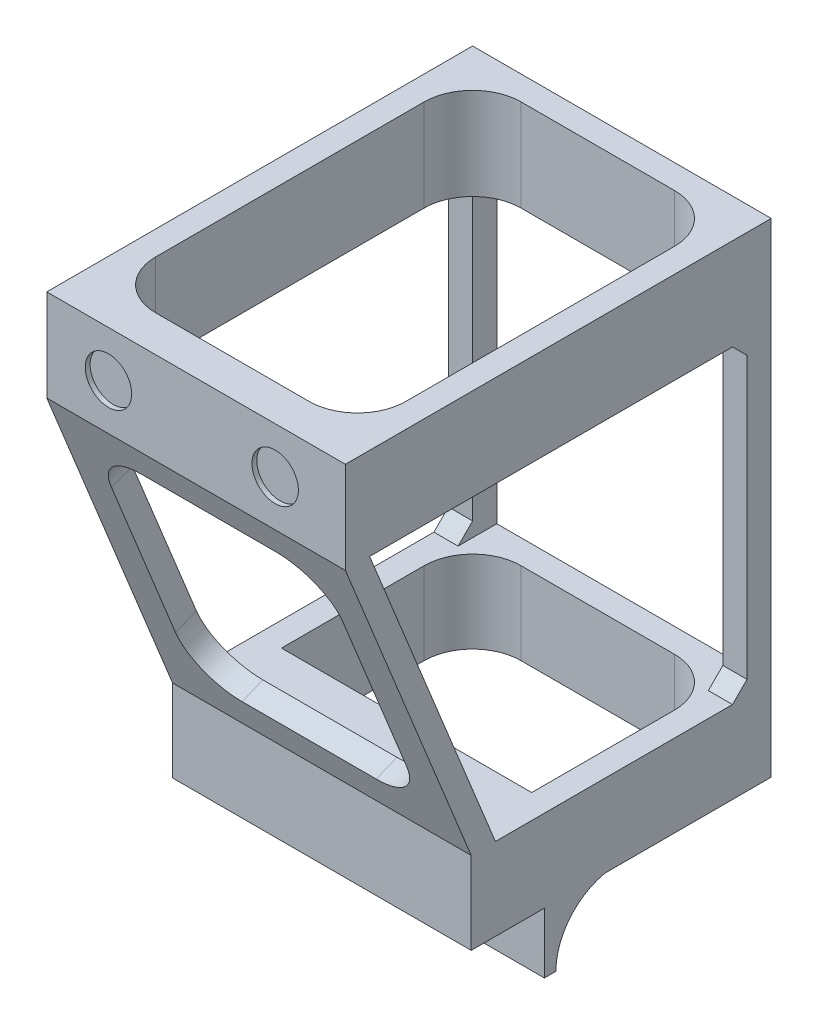
SolidWorks part; units mm, degrees
ref_plane "Front Plane" through (0, 0, 0) normal (1, 0, 0) x (0, 1, 0)
ref_plane "Top Plane" through (0, 0, 0) normal (0, 0, 1) x (0, 1, 0)
ref_plane "Right Plane" through (0, 0, 0) normal (0, 1, 0) x (-1, 0, 0)
sketch "Sketch3" plane through (0, 0, 0) normal (1, 0, 0) x (0, 1, 0)
  line L0 (0, 5) -> (0, 0)
  line L1 (0, 5) -> (17, 5)
  line L2 (17, 5) -> (81, 31)
  line L3 (81, 31) -> (100, 31)
  line L4 (0, 0) -> (17, 0)
  line L5 (17, 0) -> (81, 26)
  line L6 (81, 26) -> (100, 26)
  line L7 (100, 26) -> (100, 31)
  dimension "D1" = 100
  dimension "D2" = 26
  dimension "D3" = 17
  dimension "D4" = 19
  dimension "D5" = 5
extrude "Boss-Extrude1" add sketch "Sketch3" along normal blind 58.71
sketch "Sketch4" plane through (0, 0, 31) normal (0, 0, 1) x (1, 0, 0)
  line L0 (29.27, 23.6763) -> (29.27, 76.7509) construction
  line L1 (58.71, 100) -> (0, 100) construction
  line L7 (0, 81) -> (0, 17) construction
  line L8 (0, 100) -> (0, 81) construction
  circle A0 centre (12.75, 90.5) radius 4.8
  circle A1 centre (47.2, 90.5) radius 4.8
  dimension "D2" = 9.6
  dimension "D3" = 9.6
  dimension "D1" = 9.5
  dimension "D4" = 29.27
  dimension "D5" = 12.75
  dimension "D6" = 16.52
  dimension "D7" = 17.93
extrude "Cut-Extrude1" cut sketch "Sketch4" against normal blind 1
sketch "Sketch5" plane through (0, 0, 5) normal (0, 0, 1) x (1, 0, 0)
  line L0 (29.355, 100) -> (29.355, 58.2947) construction
  line L1 (58.71, 100) -> (0, 100) construction
  line L2 (58.71, 0) -> (0, 0) construction
  line L3 (0, 17) -> (0, 0) construction
  circle A0 centre (21.94, 8.5) radius 4.8
  circle A1 centre (36.94, 8.5) radius 4.8
  dimension "D4" = 9.6
  dimension "D5" = 9.6
  dimension "D1" = 15
  dimension "D2" = 21.94
  dimension "D3" = 8.5
extrude "Cut-Extrude2" cut sketch "Sketch5" against normal blind 1
sketch "Sketch6" plane through (58.71, 0, 0) normal (1, 0, 0) x (0, 1, 0)
  line L0 (81, 26) -> (81, 0)
  line L1 (81, 0) -> (100, 0)
  line L2 (100, 0) -> (100, 26)
  line L3 (81, 26) -> (100, 26)
  line L4 (81, 26) -> (100, 26) construction
extrude "Boss-Extrude3" add sketch "Sketch6" against normal up to surface (58.71 mm away) up to face at (0, 49.5, 15.5)
sketch "Sketch7" plane through (0, 0, 0) normal (0, 0, -1) x (1, 0, 0)
  line L1 (0, 0) -> (58.71, 0)
  line L2 (0, 0) -> (0, -17)
  line L3 (0, -17) -> (58.71, -17)
  line L4 (58.71, 0) -> (58.71, -17)
  line L5 (0, -81) -> (58.71, -81)
  line L6 (0, -81) -> (0, -100)
  line L7 (0, -100) -> (58.71, -100)
  line L8 (58.71, -81) -> (58.71, -100)
extrude "Boss-Extrude4" add sketch "Sketch7" along normal blind 57
sketch "Sketch8" plane through (58.71, 0, 0) normal (1, 0, 0) x (0, 1, 0)
  line L0 (100, 31) -> (81, 31) construction
  line L1 (100, -57) -> (100, 31) construction
  line L2 (100, -57) -> (81, -57) construction
  line L3 (81, 26) -> (81, -57) construction
  line L4 (17, -57) -> (0, -57) construction
  line L5 (0, 5) -> (0, -57) construction
  line L6 (17, -57) -> (17, 0) construction
  line L7 (17, 0) -> (81, 26) construction
  line L8 (81, 31) -> (17, 5) construction
  line L9 (17, 5) -> (0, 5) construction
  line L10 (100, 31) -> (81, 31)
  line L11 (100, -57) -> (100, 31)
  line L12 (100, -57) -> (81, -57)
  line L13 (81, 26) -> (81, -57)
  line L14 (17, -57) -> (0, -57)
  line L15 (0, 5) -> (0, -57)
  line L16 (17, -57) -> (17, 0)
  line L17 (17, 0) -> (81, 26)
  line L18 (81, 31) -> (17, 5)
  line L19 (17, 5) -> (0, 5)
extrude "Boss-Extrude5" add sketch "Sketch8" along normal blind 3
sketch "Sketch9" plane through (0, 0, 0) normal (0, -1, 0) x (1, 0, 0)
  line L0 (61.71, 5) -> (0, 5) construction
  line L1 (15, -2.5) -> (46.71, -2.5)
  line L2 (5, -12.5) -> (5, -42)
  line L3 (15, -52) -> (46.71, -52)
  line L4 (56.71, -12.5) -> (56.71, -42)
  line L5 (61.71, -57) -> (0, -57) construction
  line L6 (0, 5) -> (0, -57) construction
  line L7 (61.71, 5) -> (61.71, -57) construction
  arc A0 (5, -42) -> (15, -52) centre (15, -42) ccw
  arc A1 (46.71, -52) -> (56.71, -42) centre (46.71, -42) ccw
  arc A2 (46.71, -2.5) -> (56.71, -12.5) centre (46.71, -12.5) cw
  arc A3 (15, -2.5) -> (5, -12.5) centre (15, -12.5) ccw
  dimension "D5" = 10
  dimension "D1" = 7.5
  dimension "D2" = 5
  dimension "D3" = 5
  dimension "D4" = 5
extrude "Cut-Extrude3" cut sketch "Sketch9" against normal up to surface (17 mm away) up to face at (30.855, 17, -28.5)
sketch "Sketch10" plane through (0, 100, 0) normal (0, 1, 0) x (-1, 0, 0)
  line L0 (-61.71, 31) -> (0, 31) construction
  line L1 (-46.71, 23.5) -> (-15, 23.5)
  line L2 (-56.71, 13.5) -> (-56.71, -42)
  line L3 (-46.71, -52) -> (-15, -52)
  line L4 (-5, 13.5) -> (-5, -42)
  line L5 (0, -57) -> (-61.71, -57) construction
  line L6 (-61.71, -57) -> (-61.71, 31) construction
  line L7 (0, -57) -> (0, 31) construction
  arc A0 (-15, -52) -> (-5, -42) centre (-15, -42) ccw
  arc A1 (-56.71, -42) -> (-46.71, -52) centre (-46.71, -42) ccw
  arc A2 (-15, 23.5) -> (-5, 13.5) centre (-15, 13.5) cw
  arc A3 (-46.71, 23.5) -> (-56.71, 13.5) centre (-46.71, 13.5) ccw
  dimension "D5" = 10
  dimension "D1" = 7.5
  dimension "D2" = 5
  dimension "D3" = 5
  dimension "D4" = 5
extrude "Cut-Extrude4" cut sketch "Sketch10" against normal up to surface (19 mm away) up to face at (30.855, 81, -15.5)
sketch "Sketch11" plane through (0, 0.6647, -1.6362) normal (0, -0.3764, 0.9265) x (1, 0, 0)
  line L0 (61.71, 86.7115) -> (0, 86.7115) construction
  line L1 (17, 79.7115) -> (44.71, 79.7115)
  line L2 (7, 69.7115) -> (7, 34.6318)
  line L3 (17, 24.6318) -> (44.71, 24.6318)
  line L4 (54.71, 69.7115) -> (54.71, 34.6318)
  line L5 (61.71, 17.6318) -> (0, 17.6318) construction
  line L6 (0, 86.7115) -> (0, 17.6318) construction
  line L7 (61.71, 86.7115) -> (61.71, 17.6318) construction
  arc A0 (44.71, 24.6318) -> (54.71, 34.6318) centre (44.71, 34.6318) ccw
  arc A1 (44.71, 79.7115) -> (54.71, 69.7115) centre (44.71, 69.7115) cw
  arc A2 (7, 34.6318) -> (17, 24.6318) centre (17, 34.6318) ccw
  arc A3 (17, 79.7115) -> (7, 69.7115) centre (17, 69.7115) ccw
  dimension "D5" = 10
  dimension "D1" = 7
  dimension "D2" = 7
  dimension "D3" = 7
  dimension "D4" = 7
extrude "Cut-Extrude5" cut sketch "Sketch11" against normal up to surface (4.6323 mm away) up to face at (30.855, 49, 13)
sketch "Sketch12" plane through (0, 0, 0) normal (0, -1, 0) x (1, 0, 0)
  line L0 (5, -12.5) -> (5, -42) construction
  line L1 (0, -57) -> (5, -57)
  line L2 (0, -57) -> (0, -52)
  line L3 (0, -52) -> (5, -52)
  line L4 (5, -57) -> (5, -52)
  line L5 (61.71, -57) -> (56.71, -57)
  line L6 (61.71, -57) -> (61.71, -52)
  line L7 (61.71, -52) -> (56.71, -52)
  line L8 (56.71, -57) -> (56.71, -52)
  line L9 (15, -52) -> (46.71, -52) construction
  line L10 (56.71, -42) -> (56.71, -12.5) construction
extrude "Boss-Extrude6" add sketch "Sketch12" against normal blind 100
chamfer "Chamfer1" distance 3 angle 45 4 edges at (59.21, 17, -52) (2.5, 17, -52) (2.5, 81, -52) (59.21, 81, -52)
sketch "Sketch13" plane through (0, 0, 0) normal (0, -1, 0) x (1, 0, 0)
  line L0 (0, 5) -> (61.71, 5)
  line L1 (61.71, 5) -> (61.71, -12.5)
  line L2 (61.71, 5) -> (61.71, -57) construction
  line L3 (61.71, -12.5) -> (0, -12.5)
  line L4 (0, 5) -> (0, -57) construction
  line L5 (0, -12.5) -> (0, 5)
  line L6 (46.71, -2.5) -> (15, -2.5) construction
  dimension "D1" = 10
extrude "Boss-Extrude7" add sketch "Sketch13" against normal up to surface (17 mm away) up to face at (30.855, 17, -27.25)
sketch "Sketch14" plane through (0, 0, 0) normal (0, -1, 0) x (1, 0, 0)
  line L0 (0, -10.12) -> (0, -12.5)
  line L1 (0, 5) -> (0, -57) construction
  line L2 (0, -12.5) -> (24.98, -12.5)
  line L3 (24.98, -12.5) -> (24.98, -10.12)
  line L4 (24.98, -10.12) -> (0, -10.12)
  line L5 (47.69, -10.12) -> (47.69, -12.5)
  line L6 (47.69, -12.5) -> (61.71, -12.5)
  line L7 (61.71, 5) -> (61.71, -57) construction
  line L8 (61.71, -12.5) -> (61.71, -10.12)
  line L9 (61.71, -10.12) -> (47.69, -10.12)
  line L11 (5, -12.5) -> (56.71, -12.5) construction
  dimension "D1" = 2.38
  dimension "D2" = 14.02
  dimension "D3" = 24.98
extrude "Boss-Extrude8" add sketch "Sketch14" along normal blind 12.5
sketch "Sketch15" plane through (0, 0, 0) normal (-1, 0, 0) x (0, -1, 0)
  line L0 (0, -12.5) -> (12.5, -12.5)
  line L1 (0, -12.5) -> (0, -57) construction
  line L2 (0, -22.6589) -> (0, -12.5)
  arc A0 (12.5, -12.5) -> (0, -22.6589) centre (12.5, -25.2697) ccw
extrude "Boss-Extrude9" add sketch "Sketch15" against normal up to surface (5 mm away) up to face at (5, 8.5, -27.25)
sketch "Sketch16" plane through (61.71, 0, 0) normal (1, 0, 0) x (0, 1, 0)
  line L0 (-12.5, -12.5) -> (0, -12.5)
  line L1 (0, -12.5) -> (0, -22.6589)
  arc A0 (-12.5, -12.5) -> (0, -22.6589) centre (-12.5, -25.2697) cw
extrude "Boss-Extrude10" add sketch "Sketch16" against normal up to surface (5 mm away) up to face at (56.71, 8.5, -27.25)
